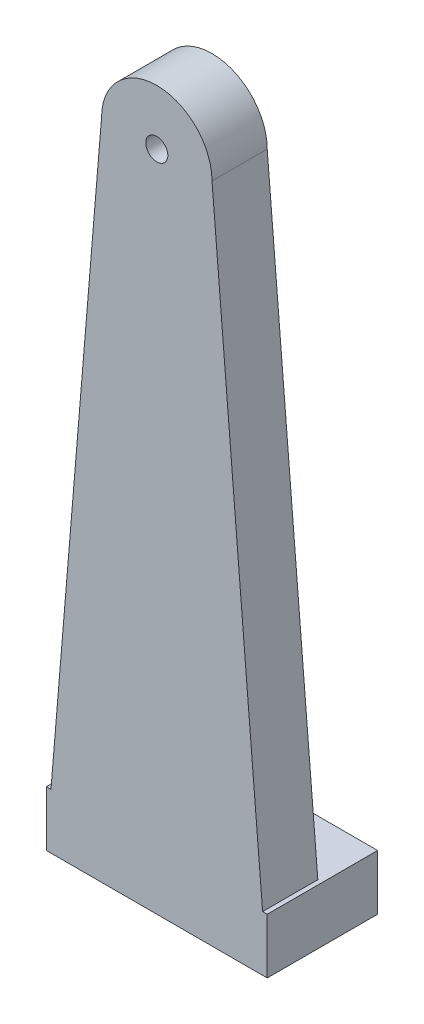
SolidWorks part; units mm, degrees
ref_plane "Alzado" through (0, 0, 0) normal (0, 0, 1) x (1, 0, 0)
ref_plane "Planta" through (0, 0, 0) normal (0, 1, 0) x (1, 0, 0)
ref_plane "Vista lateral" through (0, 0, 0) normal (1, 0, 0) x (0, 0, -1)
sketch "Croquis1" plane through (0, 0, 0) normal (0, 0, 1) x (1, 0, 0)
  line L2 (10, -25) -> (-10, -25)
  line L3 (5, 35) -> (-5, 35)
  line L4 (-5, 35) -> (-10, -25)
  line L5 (5, 35) -> (10, -25)
extrude "Saliente-Extruir1" add sketch "Croquis1" along normal blind 5
sketch "Croquis2" plane through (0, -25, 0) normal (0, -1, 0) x (-1, 0, 0)
  line L0 (10, -5) -> (-10, -5)
  line L1 (-10, -5) -> (-10, 5)
  line L2 (-10, 5) -> (10, 5)
  line L4 (10, 5) -> (10, -5)
extrude "Saliente-Extruir2" add sketch "Croquis2" against normal blind 5 contours L4 L0 L1 L2
sketch "Croquis3" plane through (0, 0, 5) normal (0, 0, 1) x (1, 0, 0)
  line L0 (5, 35) -> (-5, 35) construction
  circle A0 centre (0, 35) radius 5
  circle A1 centre (0, 35) radius 1
extrude "Saliente-Extruir4" add sketch "Croquis3" against normal blind 5
sketch "Croquis5" plane through (0, 0, 5) normal (0, 0, 1) x (1, 0, 0)
  line L0 (1, 35) -> (-1, 35) construction
  circle A0 centre (0, 35) radius 1
extrude "Cortar-Extruir1" cut sketch "Croquis5" against normal blind 5
sketch "Croquis7" plane through (0, -25, 0) normal (0, -1, 0) x (1, 0, 0)
  circle A0 centre (0, 0) radius 1
extrude "Cortar-Extruir2" cut sketch "Croquis7" against normal blind 5
